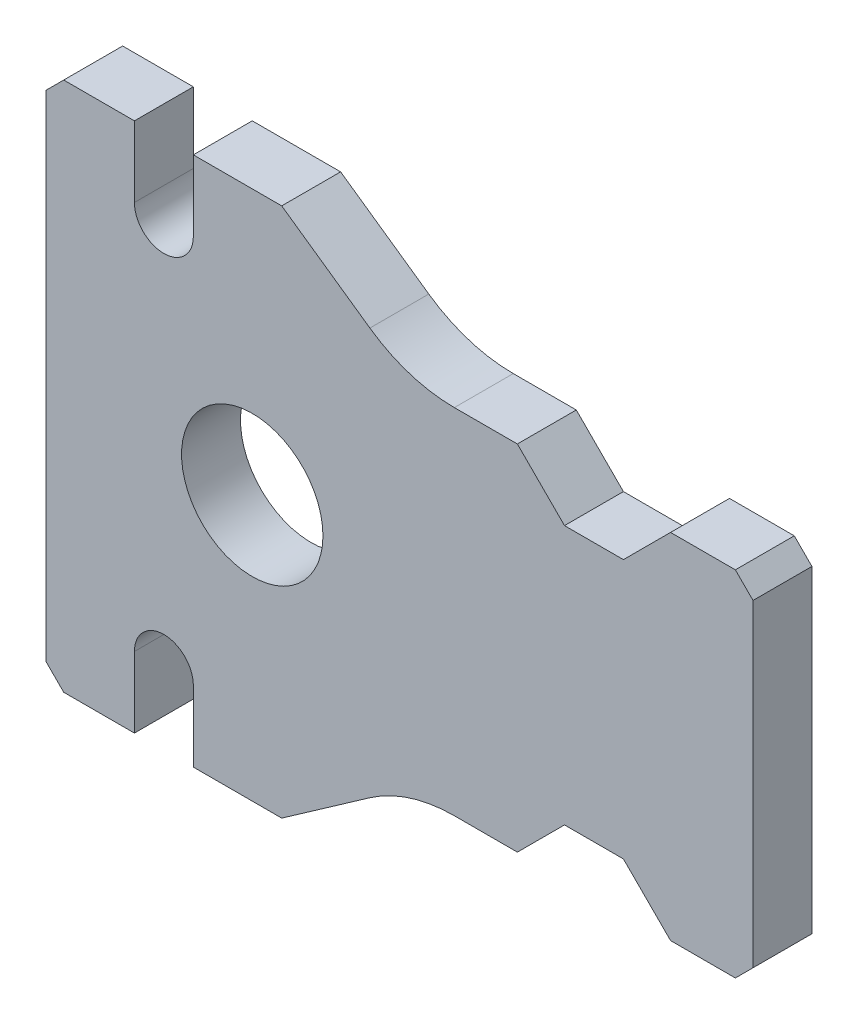
SolidWorks part; units mm, degrees
ref_plane "Front Plane" through (0, 0, 0) normal (0, 0, 1) x (1, 0, 0)
ref_plane "Top Plane" through (0, 0, 0) normal (0, 1, 0) x (1, 0, 0)
ref_plane "Right Plane" through (0, 0, 0) normal (1, 0, 0) x (0, 0, -1)
sketch "Sketch1" plane through (0, 0, 0) normal (0, 0, 1) x (1, 0, 0)
  line L0 (-35, 0) -> (85, 0) construction
  line L1 (-35, 42) -> (-35, -42)
  line L2 (-32, -45) -> (-20, -45)
  line L3 (-20, -45) -> (-20, -33)
  line L4 (-10, -33) -> (-10, -45)
  line L5 (-10, -45) -> (5, -45)
  line L6 (-35, -42) -> (-32, -45)
  line L7 (5, -45) -> (19.9653, -34.5212)
  line L8 (85, 30) -> (85, -30)
  line L9 (85, -30) -> (71, -30)
  line L10 (45, -30) -> (34.3047, -30)
  line L11 (63, -22) -> (53, -22)
  line L12 (53, -22) -> (45, -30)
  line L13 (63, -22) -> (71, -30)
  line L14 (63, 22) -> (71, 30)
  line L15 (53, 22) -> (45, 30)
  line L16 (63, 22) -> (53, 22)
  line L17 (45, 30) -> (34.3047, 30)
  line L18 (85, 30) -> (71, 30)
  line L19 (5, 45) -> (19.9653, 34.5212)
  line L20 (-35, 42) -> (-32, 45)
  line L21 (-10, 45) -> (5, 45)
  line L22 (-10, 33) -> (-10, 45)
  line L23 (-20, 45) -> (-20, 33)
  line L24 (-32, 45) -> (-20, 45)
  circle A0 centre (0, 0) radius 12
  arc A1 (34.3047, -30) -> (19.9653, -34.5212) centre (34.3047, -55) ccw
  arc A2 (-10, -33) -> (-20, -33) centre (-15, -33) ccw
  arc A3 (-10, 33) -> (-20, 33) centre (-15, 33) cw
  arc A4 (34.3047, 30) -> (19.9653, 34.5212) centre (34.3047, 55) cw
  point P3 (-35, -45)
  point P22 (0, 0)
  point P23 (0, 0)
  point P40 (-35, 45)
  dimension "D1" = 25
  dimension "D9" = 5
  dimension "D15" = 24
  dimension "D2" = 42
  dimension "D4" = 30
  dimension "D5" = 32
  dimension "D6" = 22
  dimension "D7" = 22
  dimension "D8" = 35
  dimension "D10" = 12
  dimension "D11" = 40
  dimension "D12" = 35
  dimension "D13" = 20
  dimension "D14" = 120
extrude "Boss-Extrude1" add sketch "Sketch1" along normal blind 10
chamfer "Chamfer1" distance 3 angle 45 2 edges at (85, -30, 5) (85, 30, 5)
